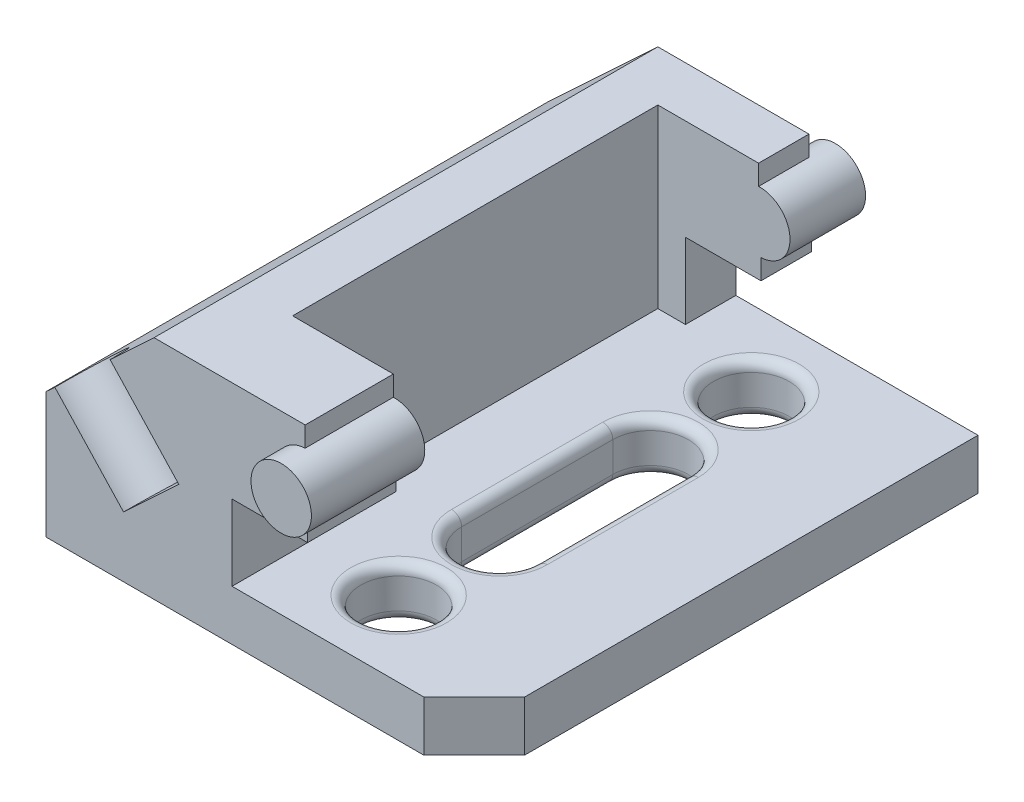
SolidWorks part; units mm, degrees
material "Alliage 1060"
ref_plane "Plan de face" through (0, 0, 0) normal (0, 0, 1) x (1, 0, 0)
ref_plane "Plan de dessus" through (0, 0, 0) normal (0, 1, 0) x (1, 0, 0)
ref_plane "Plan de droite" through (0, 0, 0) normal (1, 0, 0) x (0, 0, -1)
sketch "Esquisse1" plane through (0, 0, 0) normal (0, 0, 1) x (1, 0, 0)
  line L0 (0, 0) -> (-85, 0)
  line L1 (-85, 0) -> (-85, 25)
  line L2 (-85, 25) -> (-63.5526, 45)
  line L3 (-63.5526, 45) -> (-33.5526, 45)
  line L4 (-33.5526, 45) -> (-33.5526, 40.9981)
  line L5 (-33.3127, 35.0029) -> (-33.3127, 30.9643) construction
  line L6 (-85, 25) -> (-85, 26.0884) construction
  line L7 (-33.0727, 29.0077) -> (-33.0727, 25.0058)
  line L8 (-33.0727, 25.0058) -> (-48.0727, 25.0058)
  line L9 (-48.0727, 25.0058) -> (-48.0727, 10)
  line L10 (-48.0727, 10) -> (0, 10)
  line L11 (0, 10) -> (0, 0)
  circle A0 centre (-33.3127, 35.0029) radius 6
  dimension "D1" = 12
  dimension "D2" = 85
  dimension "D3" = 30
  dimension "D4" = 47
  dimension "D5" = 15
  dimension "D6" = 20
  dimension "D7" = 25
  dimension "D8" = 20
  dimension "D9" = 10
  dimension "D10" = 10
extrude "Boss.-Extru.1" add sketch "Esquisse1" along normal blind 110 contours A0 L4 L3 L2 L1 L0 L11 L10 L9 L8 L7 | A0
sketch "Esquisse2" plane through (0, 0, 0) normal (0, 0, -1) x (-1, 0, 0)
  line L0 (33.5526, 45) -> (33.5526, 40.9981) construction
  line L1 (63.5526, 45) -> (33.5526, 45) construction
  line L2 (85, 25) -> (63.5526, 45) construction
  line L3 (85, 0) -> (85, 25) construction
  line L4 (0, 0) -> (85, 0) construction
  line L5 (0, 10) -> (0, 0) construction
  line L6 (48.0727, 10) -> (0, 10) construction
  line L7 (48.0727, 25.0058) -> (48.0727, 10) construction
  line L8 (33.0727, 25.0058) -> (48.0727, 25.0058) construction
  line L9 (33.0727, 29.0077) -> (33.0727, 25.0058) construction
  line L10 (33.5526, 45) -> (33.5526, 40.9981)
  line L11 (63.5526, 45) -> (33.5526, 45)
  line L12 (85, 25) -> (63.5526, 45)
  line L13 (85, 0) -> (85, 25)
  line L14 (0, 0) -> (85, 0)
  line L15 (0, 10) -> (0, 0)
  line L16 (48.0727, 10) -> (0, 10)
  line L17 (48.0727, 25.0058) -> (48.0727, 10)
  line L18 (33.0727, 25.0058) -> (48.0727, 25.0058)
  line L19 (33.0727, 29.0077) -> (33.0727, 25.0058)
  circle A1 centre (33.3127, 35.0029) radius 6
  arc A2 (33.0727, 29.0077) -> (33.5526, 40.9981) centre (33.3127, 35.0029) ccw
  dimension "D1" = 0
extrude "Enlèv. mat.-Extru.1" cut sketch "Esquisse2" against normal blind 5
sketch "Esquisse3" plane through (0, 0, 110) normal (0, 0, 1) x (1, 0, 0)
  line L0 (-33.5526, 45) -> (-33.5526, 40.9981) construction
  line L1 (-63.5526, 45) -> (-33.5526, 45) construction
  line L2 (-85, 25) -> (-63.5526, 45) construction
  line L3 (-85, 0) -> (-85, 25) construction
  line L4 (0, 0) -> (-85, 0) construction
  line L5 (0, 10) -> (0, 0) construction
  line L6 (-48.0727, 10) -> (0, 10) construction
  line L7 (-48.0727, 25.0058) -> (-48.0727, 10) construction
  line L8 (-33.0727, 25.0058) -> (-48.0727, 25.0058) construction
  line L9 (-33.0727, 29.0077) -> (-33.0727, 25.0058) construction
  line L10 (-33.5526, 45) -> (-33.5526, 40.9981)
  line L11 (-63.5526, 45) -> (-33.5526, 45)
  line L12 (-85, 25) -> (-63.5526, 45)
  line L13 (-85, 0) -> (-85, 25)
  line L14 (0, 0) -> (-85, 0)
  line L15 (0, 10) -> (0, 0)
  line L16 (-48.0727, 10) -> (0, 10)
  line L17 (-48.0727, 25.0058) -> (-48.0727, 10)
  line L18 (-33.0727, 25.0058) -> (-48.0727, 25.0058)
  line L19 (-33.0727, 29.0077) -> (-33.0727, 25.0058)
  circle A1 centre (-33.3127, 35.0029) radius 6
  arc A2 (-33.5526, 40.9981) -> (-33.0727, 29.0077) centre (-33.3127, 35.0029) ccw
  dimension "D1" = 0
extrude "Enlèv. mat.-Extru.2" cut sketch "Esquisse3" against normal blind 5
sketch "Esquisse5" plane through (0, 45, 0) normal (0, 1, 0) x (1, 0, 0)
  line L0 (-53.5526, -15) -> (-15.5658, -15)
  line L3 (-15.5658, -15) -> (-15.5658, -87.5)
  line L4 (-15.5658, -87.5) -> (-53.5526, -87.5)
  line L6 (-63.5526, -5) -> (-33.5526, -5) construction
  line L7 (-53.5526, -15) -> (-53.5526, -87.5)
  line L8 (-63.5526, -105) -> (-63.5526, -5) construction
  dimension "D1" = 10
  dimension "D2" = 10
  dimension "D3" = 72.5
extrude "Enlèv. mat.-Extru.4" cut sketch "Esquisse5" against normal up to surface (35 mm away) up to face at (-24.0364, 10, 55)
sketch "Esquisse6" plane through (-52.0049, 55.7684, 0) normal (-0.682, 0.7314, 0) x (0.7314, 0.682, 0)
  line L0 (-15.7895, -105) -> (-45.1151, -105) construction
  line L1 (-15.7895, -105) -> (-15.7895, -5) construction
  circle A0 centre (-35.2145, -105) radius 7.5
  dimension "D1" = 19.425
extrude "Enlèv. mat.-Extru.5" cut sketch "Esquisse6" against normal blind 20
sketch "Esquisse7" plane through (0, 10, 0) normal (0, 1, 0) x (1, 0, 0)
  line L0 (-30, -40) -> (-30, -70)
  line L1 (-37.5, -40) -> (-37.5, -70)
  line L2 (-22.5, -40) -> (-22.5, -70)
  line L3 (-10, -105) -> (0, -95)
  line L4 (0, -105) -> (-48.0727, -105) construction
  line L5 (0, -105) -> (0, -5) construction
  line L6 (-10, -105) -> (0, -105)
  line L7 (0, -105) -> (0, -95)
  circle A0 centre (-30, -20) radius 7.5
  circle A1 centre (-30, -90) radius 7.5
  arc A2 (-22.5, -40) -> (-37.5, -40) centre (-30, -40) ccw
  arc A3 (-37.5, -70) -> (-22.5, -70) centre (-30, -70) ccw
  dimension "D3" = 7.5
  dimension "D4" = 15
  dimension "D5" = 15
  dimension "D1" = 30
  dimension "D2" = 0
  dimension "D6" = 15
  dimension "D7" = 20
  dimension "D8" = 20
  dimension "D9" = 15
  dimension "D10" = 45
  dimension "D11" = 10
extrude "Enlèv. mat.-Extru.6" cut sketch "Esquisse7" against normal blind 20
fillet "Congé1" radius 2 6 edges at (-30, 10, 32.5) (-37.5, 10, 55) (-30, 10, 77.5) (-30, 10, 97.5) (-22.5, 10, 55) (-30, 10, 27.5)
fillet "Congé2" radius 2 6 edges at (-30, 0, 77.5) (-37.5, 0, 55) (-30, 0, 32.5) (-22.5, 0, 20) (-22.5, 0, 55) (-22.5, 0, 90)
equation "\"A\" = 85"
equation "\"B\" = 72.5"
equation "\"C\"= 47"
equation "\"D2@Esquisse1\"=\"A\""
equation "\"D4@Esquisse1\"=\"C\""
equation "\"D1@Esquisse6\"=38.85/2"
equation "\"D3@Esquisse5\"=\"B\""
